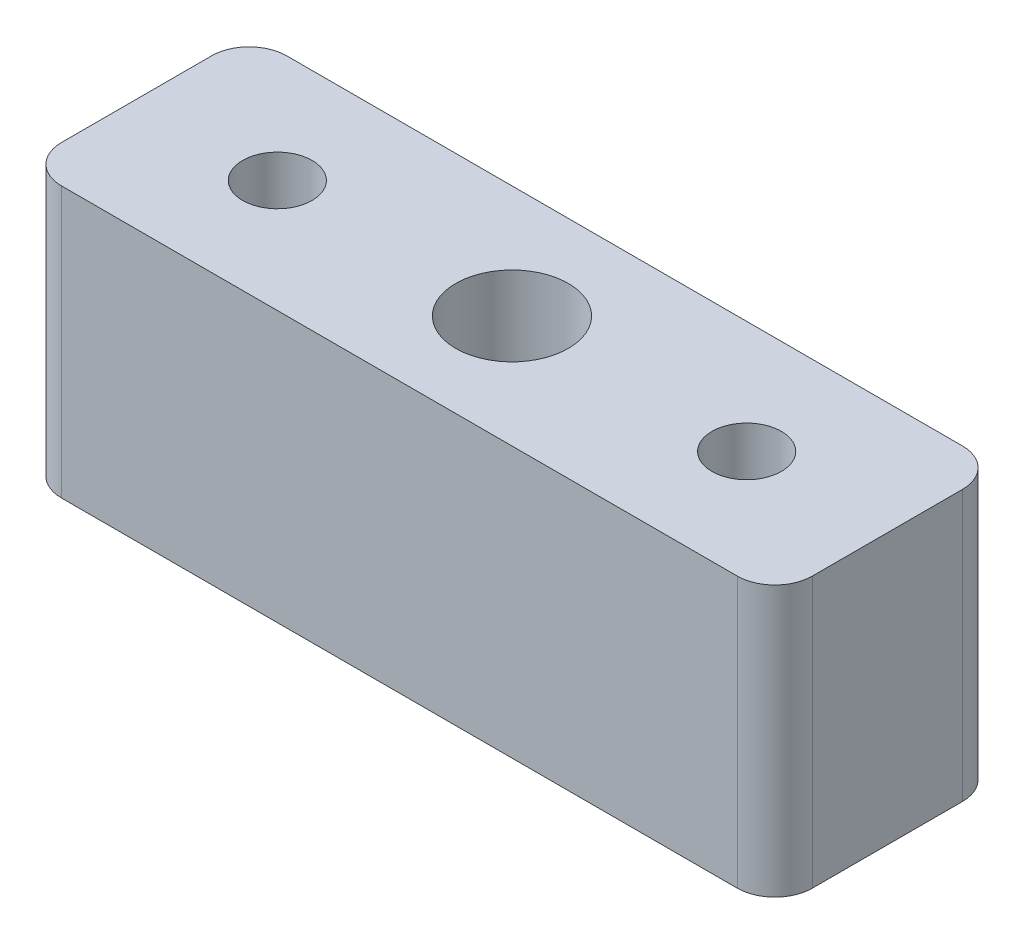
SolidWorks part; units mm, degrees
material "ABS"
ref_plane "前视基准面" through (0, 0, 0) normal (0, 0, 1) x (1, 0, 0)
ref_plane "上视基准面" through (0, 0, 0) normal (0, 1, 0) x (1, 0, 0)
ref_plane "右视基准面" through (0, 0, 0) normal (1, 0, 0) x (0, 0, -1)
other "Configuration Table"
sketch "草图1" plane through (0, 0, 0) normal (0, 1, 0) x (1, 0, 0)
  line L0 (0, -17.162) -> (0, 15.8514) construction
  line L1 (-20, 6) -> (20, 6)
  line L2 (-20, 6) -> (-20, -6)
  line L3 (-20, -6) -> (20, -6)
  line L4 (20, 6) -> (20, -6)
  line L5 (-20, 6) -> (20, -6) construction
  line L6 (-20, -6) -> (20, 6) construction
  circle A0 centre (-12.5, 0) radius 1.85
  circle A1 centre (12.5, 0) radius 1.85
  point P0 (0, 0)
  dimension "D3" = 3.7
  dimension "D1" = 40
  dimension "D2" = 12
  dimension "D4" = 25
extrude "凸台-拉伸1" add sketch "草图1" along normal blind 14.4
fillet "圆角1" radius 2 4 edges at (20, 7.2, 6) (-20, 7.2, -6) (20, 7.2, -6) (-20, 7.2, 6)
sketch "草图2" plane through (0, 14.4, 0) normal (0, 1, 0) x (1, 0, 0)
  circle A0 centre (0, 0) radius 3
  dimension "D1" = 6
extrude "切除-拉伸1" cut sketch "草图2" against normal blind 20
